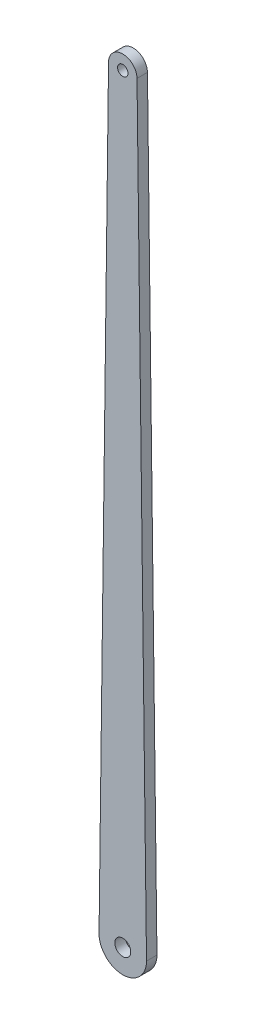
SolidWorks part; units mm, degrees
material "Custom Plastic"
ref_plane "Front Plane" through (0, 0, 0) normal (0, 0, 1) x (1, 0, 0)
ref_plane "Top Plane" through (0, 0, 0) normal (0, 1, 0) x (1, 0, 0)
ref_plane "Right Plane" through (0, 0, 0) normal (1, 0, 0) x (0, 0, -1)
sketch "Sketch1" plane through (0, 0, 0) normal (0, 0, 1) x (1, 0, 0)
  line L0 (-12.5, 0) -> (12.5, 0)
  line L1 (12.5, 0) -> (7.4994, 400.0937)
  line L2 (-7.4994, 400.0937) -> (-12.5, 0)
  arc A0 (-7.4994, 400.0937) -> (7.4994, 400.0937) centre (0, 400) cw
  circle A1 centre (0, 0) radius 12.5
  circle A2 centre (0, 400) radius 2.75
  circle A3 centre (0, 0) radius 4.2
  point P4 (0, 0)
  dimension "D1" = 7.5
  dimension "D2" = 400
  dimension "D5" = 25
  dimension "D4" = 5.5
  dimension "D6" = 8.4
  dimension "D3" = 25
extrude "Boss-Extrude1" add sketch "Sketch1" along normal blind 5.5 contours A1 L1 A0 L2 A2 | A3 L0 L1 A1 L2 | A3 L0 A1
